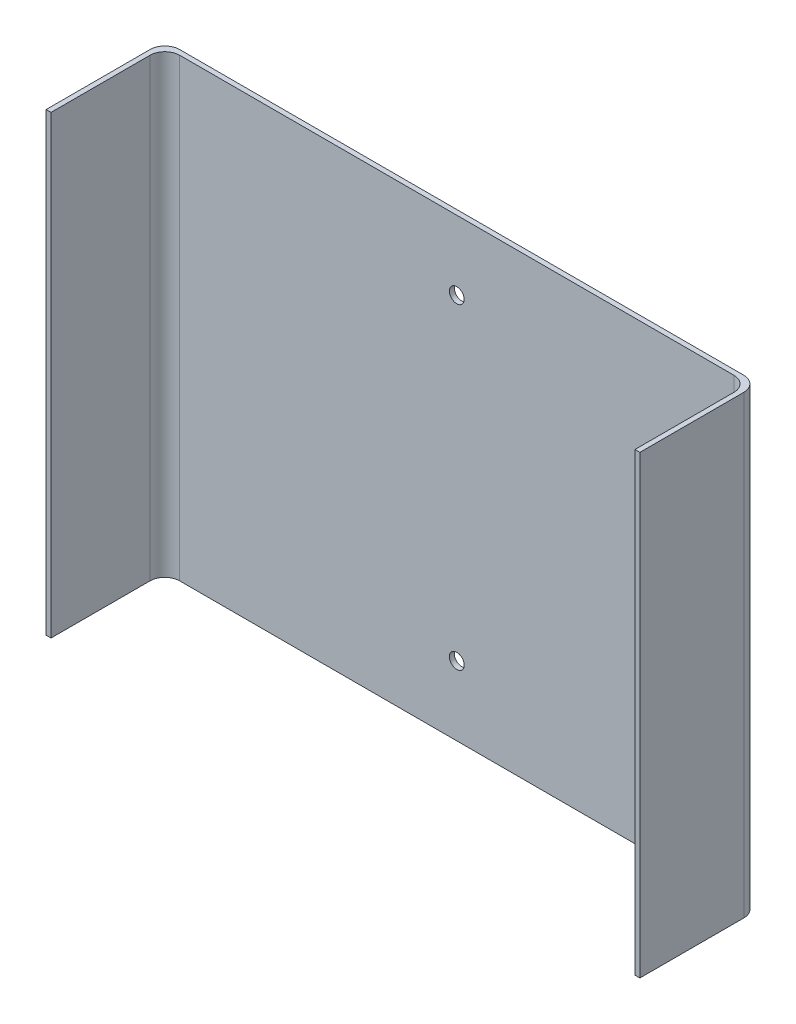
SolidWorks part; units mm, degrees
ref_plane "Front Plane" through (0, 0, 0) normal (0, 0, 1) x (1, 0, 0)
ref_plane "Top Plane" through (0, 0, 0) normal (0, 1, 0) x (1, 0, 0)
ref_plane "Right Plane" through (0, 0, 0) normal (1, 0, 0) x (0, 0, -1)
sketch "Sketch1" plane through (0, 0, 0) normal (0, 0, 1) x (1, 0, 0)
  line L0 (-60, 0) -> (60, 0) construction
  line L1 (-60, 46) -> (60, 46)
  line L2 (-60, 46) -> (-60, -46)
  line L3 (-60, -46) -> (60, -46)
  line L4 (60, 46) -> (60, -46)
  line L5 (-60, 46) -> (60, -46) construction
  line L6 (-60, -46) -> (60, 46) construction
  circle A0 centre (0, -32) radius 1.5
  circle A1 centre (0, 32) radius 1.5
  point P0 (0, 0)
  dimension "D3" = 3
  dimension "D4" = 14
  dimension "D1" = 92
  dimension "D2" = 120
extrude "Boss-Extrude1" add sketch "Sketch1" along normal blind 1
sketch "Sketch2" plane through (0, 0, 1) normal (0, 0, 1) x (1, 0, 0)
  line L0 (60, 46) -> (-60, 46) construction
  line L1 (-60, -46) -> (-59, -46)
  line L2 (-60, -46) -> (-60, 46)
  line L3 (-60, 46) -> (-59, 46)
  line L4 (-59, -46) -> (-59, 46)
  dimension "D1" = 1
extrude "Boss-Extrude2" add sketch "Sketch2" along normal blind 23
fillet "Fillet1" radius 3 1 edges at (-60, 0, 0)
fillet "Fillet2" radius 3 1 edges at (-59, 0, 1)
mirror "Mirror3" about plane through (0, 0, 0) normal (1, 0, 0) of "Boss-Extrude2"
fillet "Fillet3" radius 3 2 edges at (60, 0, 0) (59, 0, 1)
